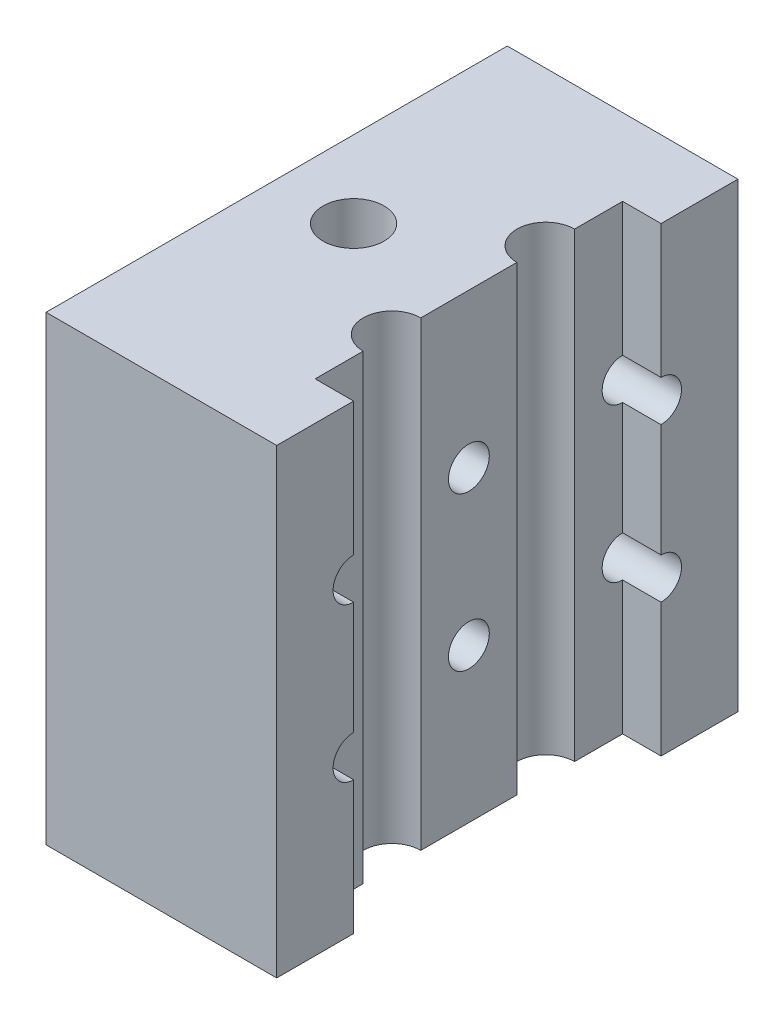
SolidWorks part; units mm, degrees
material "Copper"
ref_plane "Front Plane" through (0, 0, 0) normal (0, 0, 1) x (1, 0, 0)
ref_plane "Top Plane" through (0, 0, 0) normal (0, 1, 0) x (1, 0, 0)
ref_plane "Right Plane" through (0, 0, 0) normal (1, 0, 0) x (0, 0, -1)
sketch "Sketch1" plane through (0, 0, 0) normal (0, 1, 0) x (1, 0, 0)
  line L1 (-38.1, 38.1) -> (0, 38.1)
  line L2 (-38.1, 38.1) -> (-38.1, -38.1)
  line L3 (-38.1, -38.1) -> (0, -38.1)
  line L4 (0, 38.1) -> (0, -38.1)
  dimension "D1" = 38.1
  dimension "D2" = 76.2
  dimension "D4" = 38.1
extrude "Boss-Extrude1" add sketch "Sketch1" along normal blind 76.2
sketch "Sketch2" plane through (0, 76.2, 0) normal (0, 1, 0) x (1, 0, 0)
  line L1 (0, -38.1) -> (0, 38.1) construction
  line L2 (0, 25.4) -> (-6.35, 25.4)
  line L3 (0, 25.4) -> (0, -25.4)
  line L4 (0, -25.4) -> (-6.35, -25.4)
  line L5 (-6.35, 25.4) -> (-6.35, -25.4)
  dimension "D1" = 6.35
  dimension "D2" = 50.8
  dimension "D3" = 25.4
extrude "Cut-Extrude1" cut sketch "Sketch2" against normal through all
hole_wizard "1/4 Clearance Hole1" positions "Sketch4" profile "Sketch3" hole size "1/4" standard "ANSI Inch" end condition through all
sketch "Sketch4" plane through (0, 0, 0) normal (1, 0, 0) x (0, 0, -1)
  point P0 (0, 50.8)
  point P2 (0, 25.4)
  point P4 (-25.4, 25.4)
  point P6 (-25.4, 50.8)
  point P8 (25.4, 50.8)
  point P10 (25.4, 25.4)
sketch "Sketch3" plane through (0, 50.8, 0) normal (0, 1, 0) x (0, 0, -1)
  line L0 (0, 0) -> (0, 38.1)
  line L1 (0, 38.1) -> (3.3782, 38.1)
  line L2 (3.3782, 38.1) -> (3.3782, 0)
  line L5 (3.3782, 0) -> (0, 0)
  line L11 (0, -6.35) -> (0, 107.95) construction
  dimension "Thru Hole Dia." = 6.7564
  dimension "Thru Hole Depth" = 38.1
hole_wizard "3/8 Clearance Hole1" positions "Sketch6" profile "Sketch5" hole size "3/8" standard "ANSI Inch" end condition through all
sketch "Sketch6" plane through (0, 76.2, 0) normal (0, 1, 0) x (1, 0, 0)
  point P2 (-25.4, 0)
sketch "Sketch5" plane through (-25.4, 76.2, 0) normal (1, 0, 0) x (0, 0, 1)
  line L0 (0, 0) -> (0, 76.2)
  line L1 (0, 76.2) -> (5.0419, 76.2)
  line L2 (5.0419, 76.2) -> (5.0419, 0)
  line L5 (5.0419, 0) -> (0, 0)
  line L11 (0, -6.35) -> (0, 107.95) construction
  dimension "Thru Hole Dia." = 10.0838
  dimension "Thru Hole Depth" = 76.2
sketch "Sketch7" plane through (0, 76.2, 0) normal (0, 1, 0) x (1, 0, 0)
  line L0 (-6.35, 25.4) -> (-6.35, -25.4) construction
  line L1 (-6.35, 25.4) -> (-6.35, -25.4) construction
  circle A0 centre (-6.35, 12.7) radius 4.7625
  circle A1 centre (-6.35, -12.7) radius 4.7625
  point P6 (-6.35, 0)
  point P9 (-6.35, 0)
  dimension "D1" = 9.525
  dimension "D2" = 12.7
  dimension "D3" = 12.7
extrude "Cut-Extrude2" cut sketch "Sketch7" against normal through all
